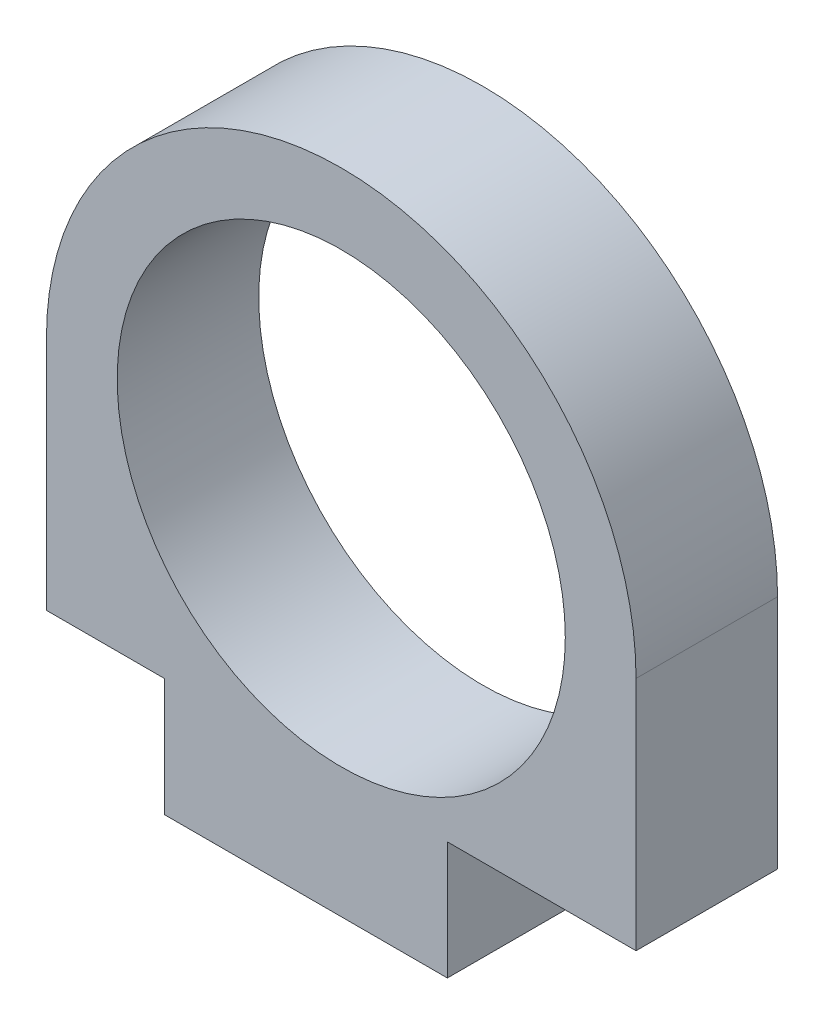
SolidWorks part; units mm, degrees
ref_plane "Alzado" through (0, 0, 0) normal (0, 0, 1) x (1, 0, 0)
ref_plane "Planta" through (0, 0, 0) normal (0, 1, 0) x (1, 0, 0)
ref_plane "Vista lateral" through (0, 0, 0) normal (1, 0, 0) x (0, 0, -1)
sketch "Croquis1" plane through (0, 0, 0) normal (0, 0, 1) x (1, 0, 0)
  line L0 (-12.5, -10) -> (12.5, -10) construction
  line L2 (-12.5, 0) -> (-12.5, -15)
  line L3 (-12.5, -15) -> (12.5, -15)
  line L4 (12.5, 0) -> (12.5, -15)
  line L6 (-12.5, -10) -> (-7.5, -10)
  line L7 (-12.5, -10) -> (-12.5, -15)
  line L8 (-12.5, -15) -> (-7.5, -15)
  line L9 (-7.5, -10) -> (-7.5, -15)
  line L10 (12.5, -10) -> (4.5, -10)
  line L11 (12.5, -10) -> (12.5, -15)
  line L12 (12.5, -15) -> (4.5, -15)
  line L13 (4.5, -10) -> (4.5, -15)
  arc A0 (12.5, 0) -> (-12.5, 0) centre (0, 0) ccw
  circle A1 centre (0, 0) radius 9.5
  point P13 (4.5, -12.5)
  dimension "D2" = 19
  dimension "D4" = 12.5
  dimension "D1" = 25
  dimension "D3" = 15
  dimension "D5" = 5
  dimension "D6" = 5
  dimension "D7" = 12
extrude "Saliente-Extruir1" add sketch "Croquis1" along normal blind 6 contours L6 L0 L10 L4 A0 L2 A1 | L0 L9 L3 L13
